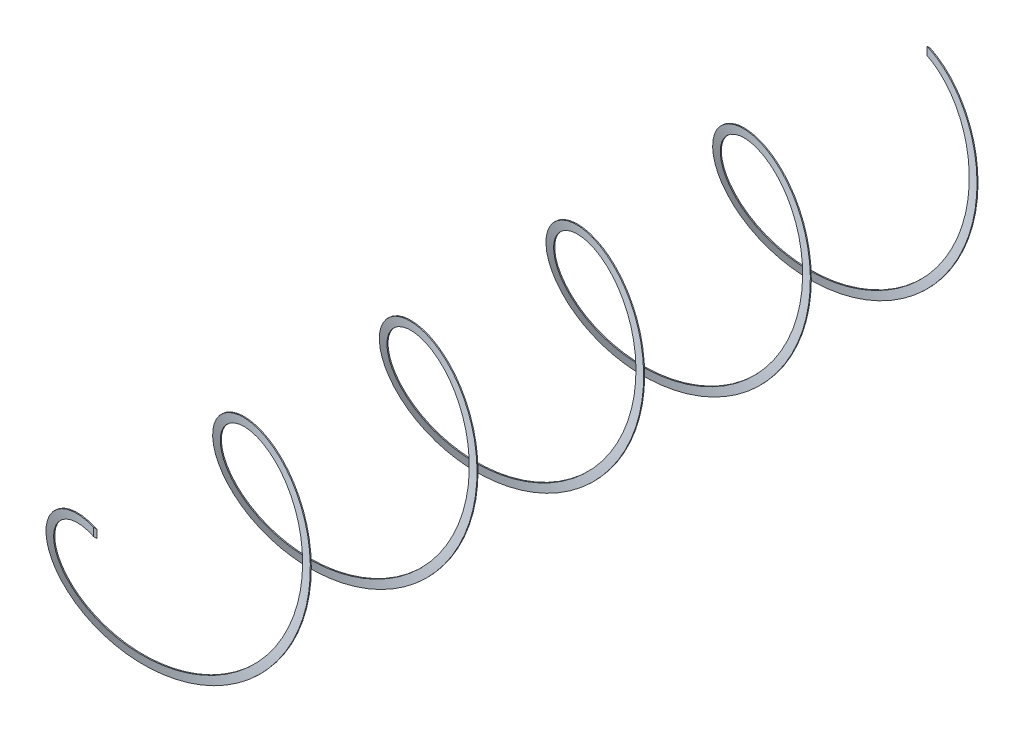
SolidWorks part; units mm, degrees
ref_plane "Front Plane" through (0, 0, 0) normal (0, 0, 1) x (1, 0, 0)
ref_plane "Top Plane" through (0, 0, 0) normal (0, 1, 0) x (1, 0, 0)
ref_plane "Right Plane" through (0, 0, 0) normal (1, 0, 0) x (0, 0, -1)
sketch "Sketch1" plane through (0, 0, 0) normal (0, 0, 1) x (1, 0, 0)
  line L0 (0, 0) -> (0, 254) construction
  line L2 (-5, 241.5) -> (5, 241.5) construction
  line L3 (-5, 241.5) -> (-5, 266.5) construction
  line L4 (-5, 266.5) -> (5, 266.5) construction
  line L5 (5, 241.5) -> (5, 266.5) construction
  line L6 (-5, 241.5) -> (5, 266.5) construction
  line L7 (-5, 266.5) -> (5, 241.5) construction
  circle A0 centre (0, 0) radius 254
  dimension "D3" = 508
  dimension "D1" = 10
  dimension "D2" = 25
curve "Helix/Spiral1" pitch 514 height 2570 turns 5
sketch "Sketch2" plane through (0, 0, 0) normal (0, 0, 1) x (1, 0, 0)
  line L1 (-5, 266.5) -> (5, 266.5)
  line L2 (-5, 266.5) -> (-5, 241.5)
  line L3 (-5, 241.5) -> (5, 241.5)
  line L4 (5, 266.5) -> (5, 241.5)
sweep "Sweep1" add profiles "Sketch2" path "Helix/Spiral1"
